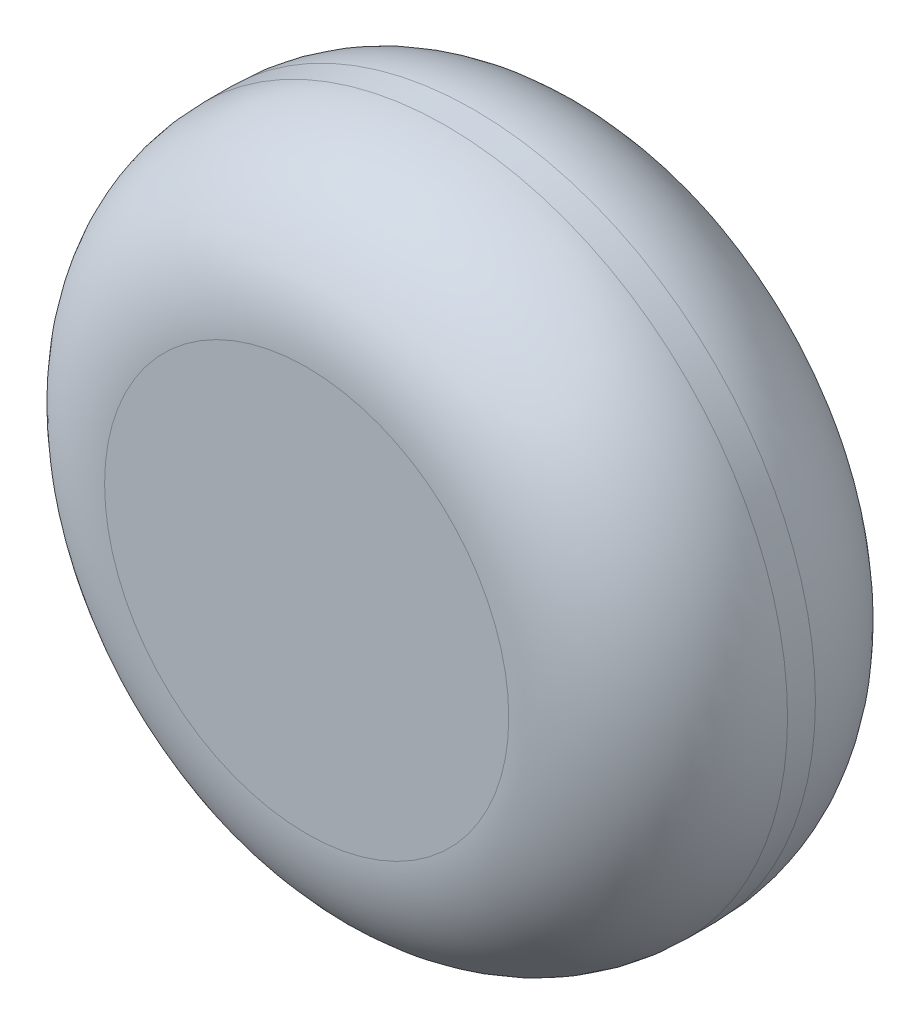
SolidWorks part; units mm, degrees
material "ABS"
ref_plane "Plan de face" through (0, 0, 0) normal (0, 0, 1) x (1, 0, 0)
ref_plane "Plan de dessus" through (0, 0, 0) normal (0, 1, 0) x (1, 0, 0)
ref_plane "Plan de droite" through (0, 0, 0) normal (1, 0, 0) x (0, 0, -1)
sketch "Esquisse1" plane through (0, 0, 0) normal (0, 0, 1) x (1, 0, 0)
  circle A0 centre (0, 0) radius 12.25
extrude "Extrusion1" add sketch "Esquisse1" along normal blind 11
fillet "Congé1" radius 5 2 edges at (12.25, 0, 0) (12.25, 0, 11)
sketch "Esquisse2" plane through (0, 0, 0) normal (0, 1, 0) x (1, 0, 0)
  line L0 (7.25, 0) -> (-7.25, 0) construction
  line L1 (-7.25, -11) -> (7.25, -11) construction
  circle A0 centre (0, 0.5) radius 0.5
  circle A1 centre (0, -11.5) radius 0.5
